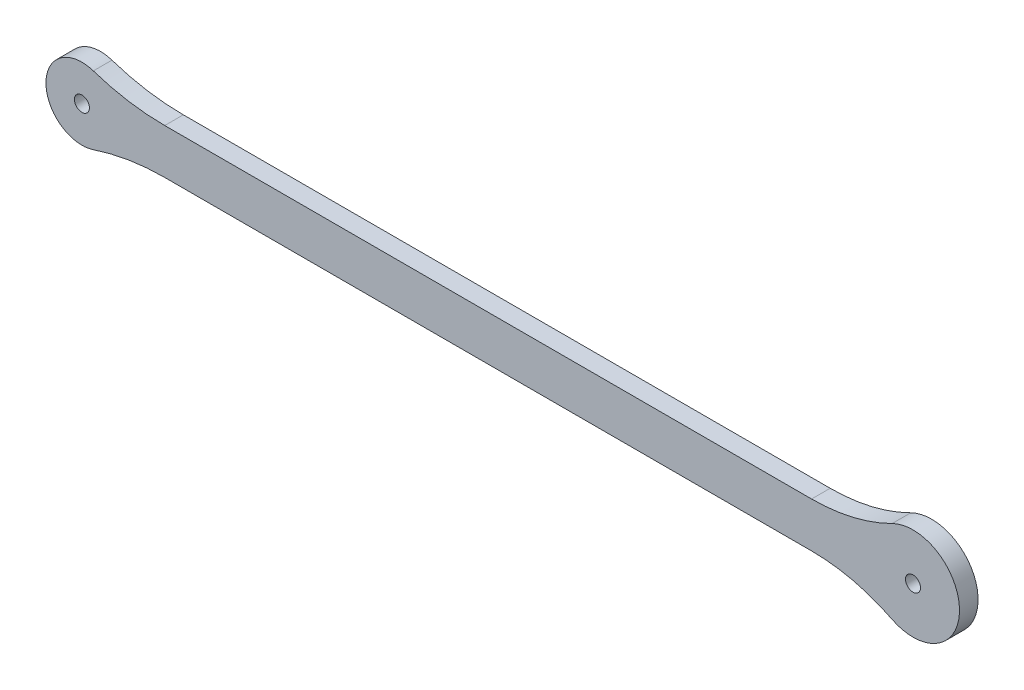
SolidWorks part; units mm, degrees
ref_plane "Front Plane" through (0, 0, 0) normal (0, 0, 1) x (1, 0, 0)
ref_plane "Top Plane" through (0, 0, 0) normal (0, 1, 0) x (1, 0, 0)
ref_plane "Right Plane" through (0, 0, 0) normal (1, 0, 0) x (0, 0, -1)
sketch "Sketch1" plane through (0, 0, 0) normal (0, 0, 1) x (1, 0, 0)
  line L2 (104.7469, 7.5) -> (-110.9521, 7.5)
  line L3 (-110.9521, -7.5) -> (104.7469, -7.5)
  line L4 (-138.57, 0) -> (138.57, 0) construction
  circle A0 centre (-138.57, 0) radius 2.5
  circle A1 centre (138.57, 0) radius 2.5
  circle A2 centre (138.57, 0) radius 2.5
  arc A4 (131.6262, -13.8576) -> (131.6262, 13.8576) centre (138.57, 0) ccw
  arc A6 (-134.7606, 11.3793) -> (-110.9521, 7.5) centre (-110.9521, 82.5) ccw
  arc A7 (-134.7606, 11.3793) -> (-134.7606, -11.3793) centre (-138.57, 0) ccw
  arc A8 (-110.9521, -7.5) -> (-134.7606, -11.3793) centre (-110.9521, -82.5) ccw
  arc A9 (131.6262, -13.8576) -> (104.7469, -7.5) centre (104.7469, -67.5) ccw
  arc A10 (104.7469, 7.5) -> (131.6262, 13.8576) centre (104.7469, 67.5) ccw
  dimension "D4" = 12
  dimension "D5" = 5
  dimension "D6" = 75
  dimension "D7" = 15.5
  dimension "D8" = 60
  dimension "D9" = 5
  dimension "D10" = 5
  dimension "D1" = 277.14
  dimension "D2" = 15
  dimension "D3" = 7.5
extrude "Boss-Extrude1" add sketch "Sketch1" along normal blind 6.2
